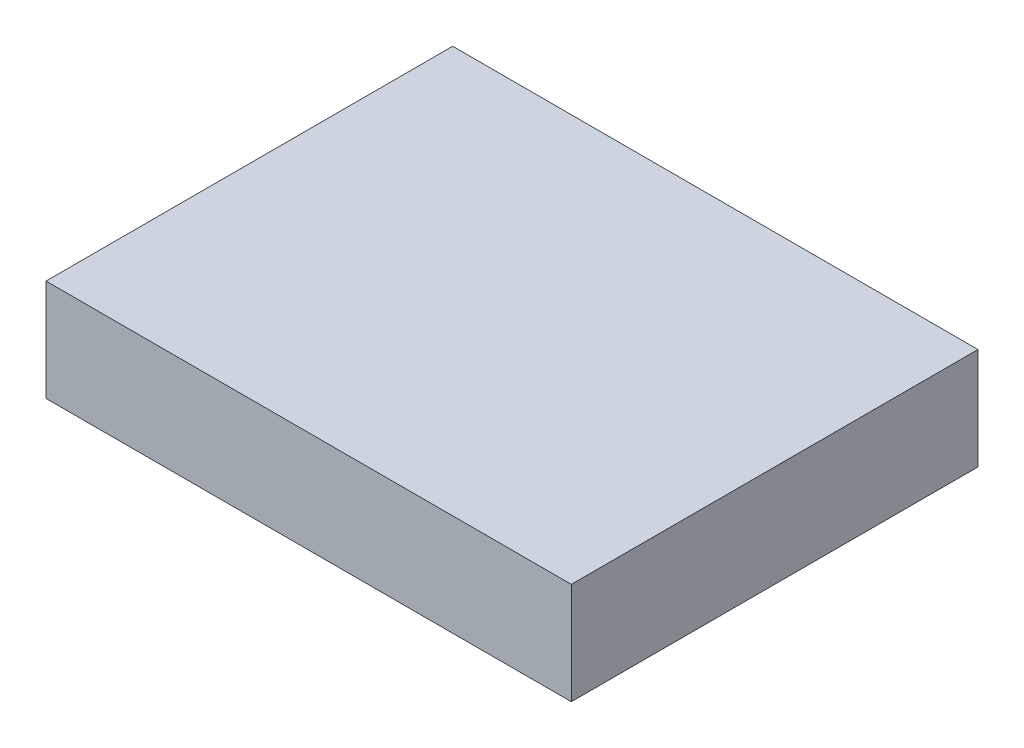
SolidWorks part; units mm, degrees
ref_plane "Front Plane" through (0, 0, 0) normal (0, 0, 1) x (1, 0, 0)
ref_plane "Top Plane" through (0, 0, 0) normal (0, 1, 0) x (1, 0, 0)
ref_plane "Right Plane" through (0, 0, 0) normal (1, 0, 0) x (0, 0, -1)
sketch "Sketch1" plane through (0, 0, 0) normal (0, 1, 0) x (1, 0, 0)
  line L1 (7.75, -6) -> (-7.75, -6)
  line L2 (7.75, -6) -> (7.75, 6)
  line L3 (7.75, 6) -> (-7.75, 6)
  line L4 (-7.75, -6) -> (-7.75, 6)
  line L5 (7.75, -6) -> (-7.75, 6) construction
  line L6 (7.75, 6) -> (-7.75, -6) construction
  point P0 (0, 0)
  dimension "D1" = 12
  dimension "D2" = 15.5
extrude "Boss-Extrude1" add sketch "Sketch1" along normal blind 3
